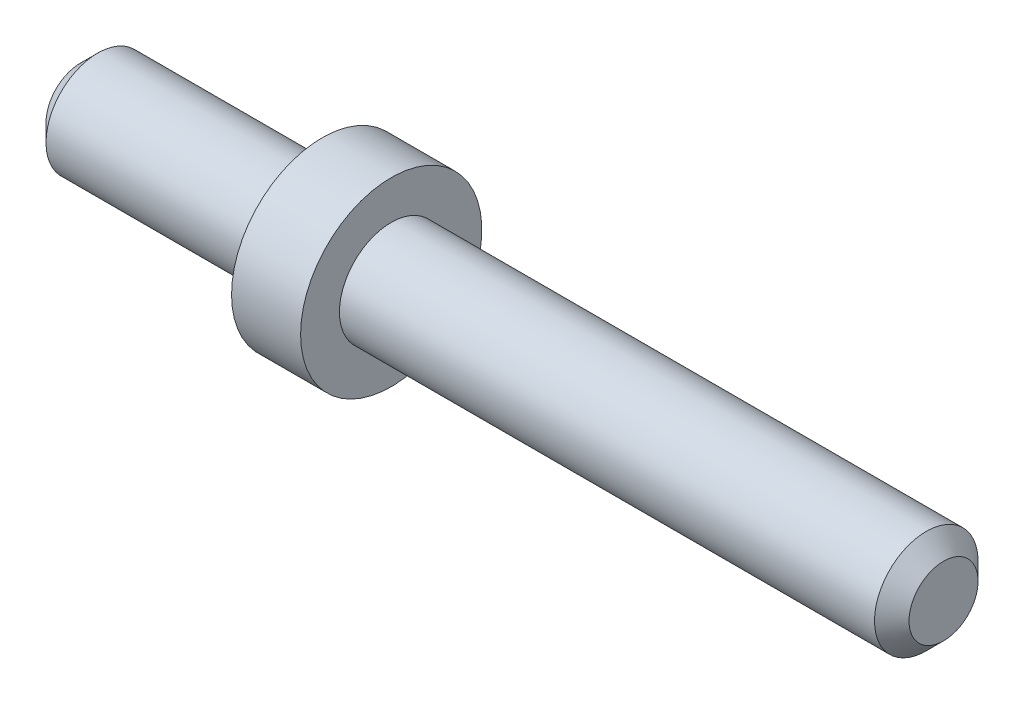
SolidWorks part; units mm, degrees
material "Простая углеродистая сталь"
ref_plane "Спереди" through (0, 0, 0) normal (0, 0, 1) x (1, 0, 0)
ref_plane "Сверху" through (0, 0, 0) normal (0, 1, 0) x (1, 0, 0)
ref_plane "Справа" through (0, 0, 0) normal (1, 0, 0) x (0, 0, -1)
other "Табл. исп."
sketch "Эскиз1" plane through (0, 0, 0) normal (0, 0, 1) x (1, 0, 0)
  line L0 (0, 0) -> (140.0144, 0) construction
  line L1 (0, 0) -> (0, 2)
  line L2 (1, 3) -> (14, 3)
  line L3 (14, 3) -> (14, 5.25)
  line L4 (14, 5.25) -> (18, 5.25)
  line L5 (18, 5.25) -> (18, 3)
  line L6 (18, 3) -> (49, 3)
  line L7 (50, 2) -> (50, 0)
  line L8 (50, 0) -> (0, 0)
  line L9 (0, 2) -> (1, 3)
  line L10 (49, 3) -> (50, 2)
  point P4 (0, 3)
  point P9 (50, 3)
  dimension "D1" = 6
  dimension "D2" = 6
  dimension "D3" = 10.5
  dimension "D4" = 4
  dimension "L" = 14
  dimension "L1" = 50
  dimension "D7" = 1
  dimension "D8" = 45
  dimension "D9" = 1
  dimension "D10" = 45
revolve "Повернуть1" add sketch "Эскиз1" angle 360 about L0
